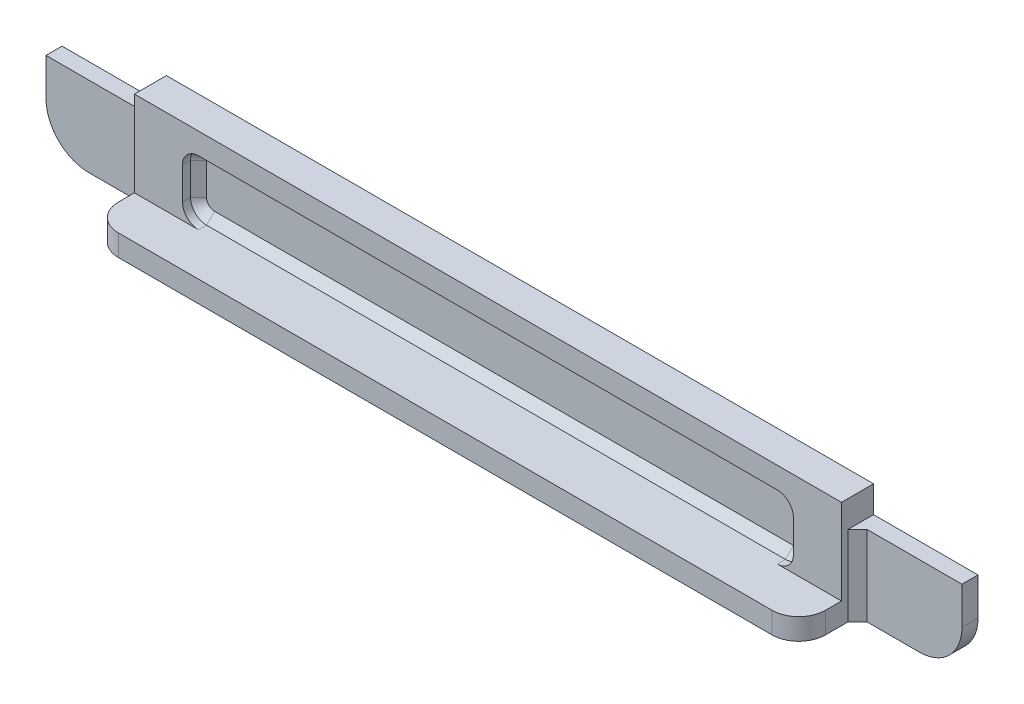
SolidWorks part; units mm, degrees
material "ABS"
ref_plane "Front Plane" through (0, 0, 0) normal (0, 0, 1) x (1, 0, 0)
ref_plane "Top Plane" through (0, 0, 0) normal (0, 1, 0) x (1, 0, 0)
ref_plane "Right Plane" through (0, 0, 0) normal (1, 0, 0) x (0, 0, -1)
sketch "Sketch1" plane through (0, 0, 0) normal (0, 0, 1) x (1, 0, 0)
  line L1 (-85.725, 10) -> (85.725, 10)
  line L2 (-85.725, 10) -> (-85.725, -10)
  line L3 (-85.725, -10) -> (85.725, -10)
  line L4 (85.725, 10) -> (85.725, -10)
  line L5 (-85.725, 10) -> (85.725, -10) construction
  line L6 (-85.725, -10) -> (85.725, 10) construction
  point P0 (0, 0)
  dimension "D1" = 171.45
  dimension "D2" = 20
extrude "Boss-Extrude1" add sketch "Sketch1" along normal blind 6
sketch "Sketch2" plane through (0, 0, 6) normal (0, 0, 1) x (1, 0, 0)
  line L1 (-85.725, -10) -> (-66.175, -10)
  line L2 (-85.725, -10) -> (-85.725, 5)
  line L3 (-85.725, 5) -> (-66.175, 5)
  line L4 (-66.175, -10) -> (-66.175, 5)
  line L5 (85.725, -10) -> (66.175, -10)
  line L6 (85.725, -10) -> (85.725, 5)
  line L7 (85.725, 5) -> (66.175, 5)
  line L8 (66.175, -10) -> (66.175, 5)
  dimension "D1" = 15
  dimension "D2" = 19.55
  dimension "D3" = 19.55
extrude "Cut-Extrude1" cut sketch "Sketch2" against normal blind 3
sketch "Sketch3" plane through (0, 0, 6) normal (0, 0, 1) x (1, 0, 0)
  line L1 (-85.725, 10) -> (-66.175, 10)
  line L2 (-85.725, 10) -> (-85.725, 5)
  line L3 (-85.725, 5) -> (-66.175, 5)
  line L4 (-66.175, 10) -> (-66.175, 5)
  line L5 (85.725, 10) -> (66.175, 10)
  line L6 (85.725, 10) -> (85.725, 5)
  line L7 (85.725, 5) -> (66.175, 5)
  line L8 (66.175, 10) -> (66.175, 5)
extrude "Cut-Extrude2" cut sketch "Sketch3" against normal blind 13
chamfer "Chamfer1" distance 1.8 angle 45 2 edges at (66.175, -2.5, 3) (-66.175, -2.5, 3)
sketch "Sketch4" plane through (0, 0, 6) normal (0, 0, 1) x (1, 0, 0)
  line L0 (66.175, 10) -> (66.175, -10) construction
  line L1 (-66.175, -10) -> (66.175, -10)
  line L2 (-66.175, -10) -> (-66.175, -6)
  line L3 (-66.175, -6) -> (66.175, -6)
  line L4 (66.175, -10) -> (66.175, -6)
  dimension "D1" = 4
extrude "Boss-Extrude2" add sketch "Sketch4" along normal blind 8
sketch "Sketch5" plane through (0, 0, 6) normal (0, 0, 1) x (1, 0, 0)
  line L0 (66.175, -6) -> (-66.175, -6) construction
  line L1 (-54.175, -6) -> (54.175, -6)
  line L2 (-57.175, -3) -> (-57.175, 3)
  line L3 (-54.175, 6) -> (54.175, 6)
  line L4 (57.175, -3) -> (57.175, 3)
  line L5 (66.175, 10) -> (-66.175, 10) construction
  line L6 (-66.175, -6) -> (-66.175, 10) construction
  line L7 (66.175, 10) -> (66.175, -6) construction
  arc A0 (54.175, -6) -> (57.175, -3) centre (54.175, -3) ccw
  arc A1 (54.175, 6) -> (57.175, 3) centre (54.175, 3) cw
  arc A2 (-54.175, -6) -> (-57.175, -3) centre (-54.175, -3) cw
  arc A3 (-57.175, 3) -> (-54.175, 6) centre (-54.175, 3) cw
  point P18 (-57.175, -6)
  dimension "D4" = 3
  dimension "D1" = 4
  dimension "D2" = 9
  dimension "D3" = 9
extrude "Cut-Extrude3" cut sketch "Sketch5" against normal blind 3
chamfer "Chamfer2" distance 1.5 angle 45 8 edges at (0, -6, 3) (56.2963, -5.1213, 3) (-56.2963, -5.1213, 3) (57.175, 0, 3) (-57.175, 0, 3) (56.2963, 5.1213, 3) (-56.2963, 5.1213, 3) (0, 6, 3)
fillet "Fillet1" radius 8 2 edges at (85.725, -10, 1.5) (-85.725, -10, 1.5)
fillet "Fillet2" radius 5 2 edges at (66.175, -8, 14) (-66.175, -8, 14)
